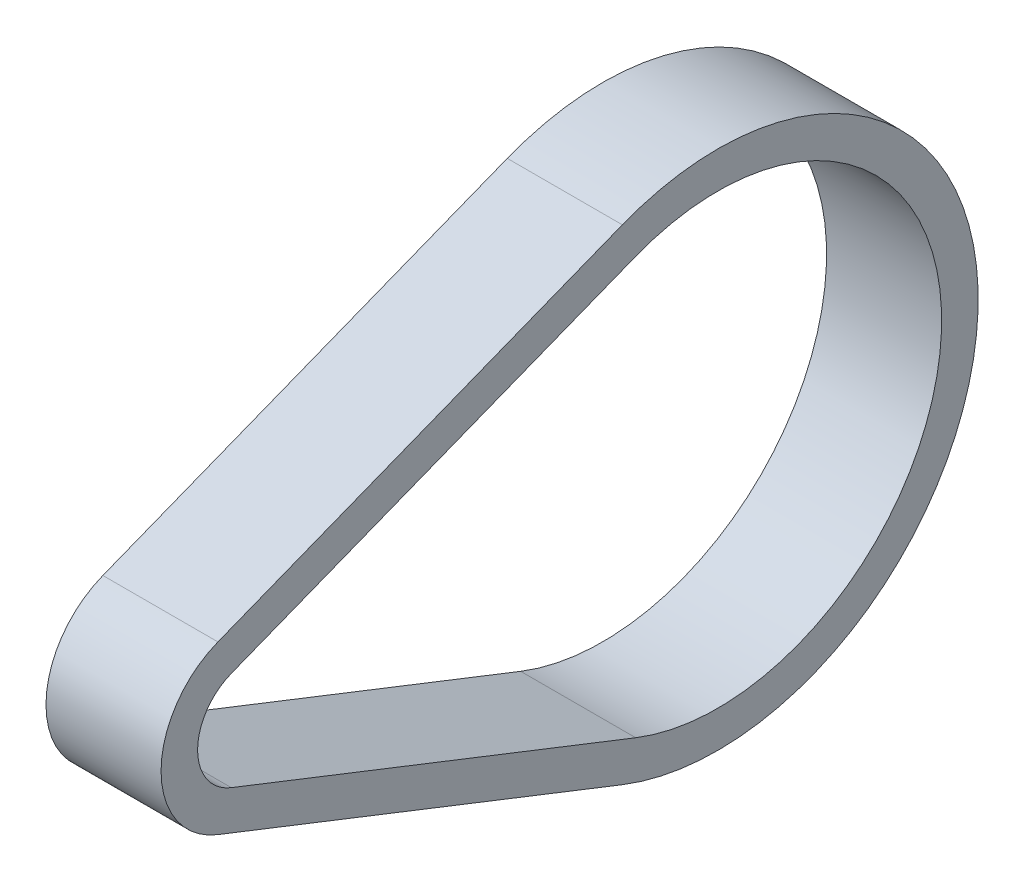
SolidWorks part; units mm, degrees
ref_plane "Front Plane" through (0, 0, 0) normal (0, 0, 1) x (1, 0, 0)
ref_plane "Top Plane" through (0, 0, 0) normal (0, 1, 0) x (1, 0, 0)
ref_plane "Right Plane" through (0, 0, 0) normal (1, 0, 0) x (0, 0, -1)
other "Bounding Box"
ref_plane "Default Plane" through (-8.9266, -12.7485, 0) normal (-0.1736, 0.9848, 0) x (0.9848, 0.1736, 0)
sketch "Sketch1" plane through (0, 0, 0) normal (1, 0, 0) x (0, 0, -1)
  line L0 (0, 0) -> (60.8736, 0) construction
  line L1 (-2.5344, 6.4463) -> (50.1896, 27.175)
  line L2 (-2.5344, -6.4463) -> (50.1896, -27.175)
  line L3 (-4.277, 10.8785) -> (48.447, 31.6073)
  line L4 (-4.277, -10.8785) -> (48.447, -31.6073)
  line L5 (-6.9266, 0) -> (-11.6891, 0) construction
  line L6 (90.0735, 0) -> (94.836, 0) construction
  arc A0 (-2.5344, 6.4463) -> (-2.5344, -6.4463) centre (0, 0) ccw
  arc A1 (50.1896, -27.175) -> (50.1896, 27.175) centre (60.8736, 0) ccw
  arc A2 (-4.277, 10.8785) -> (-4.277, -10.8785) centre (0, 0) ccw
  arc A3 (48.447, -31.6073) -> (48.447, 31.6073) centre (60.8736, 0) ccw
  dimension "D2" = 4.7625
  dimension "D4" = 13.8532
  dimension "D5" = 58.3997
  dimension "D1" = 60.8736
extrude "Boss-Extrude1" add sketch "Sketch1" along normal mid plane 15
